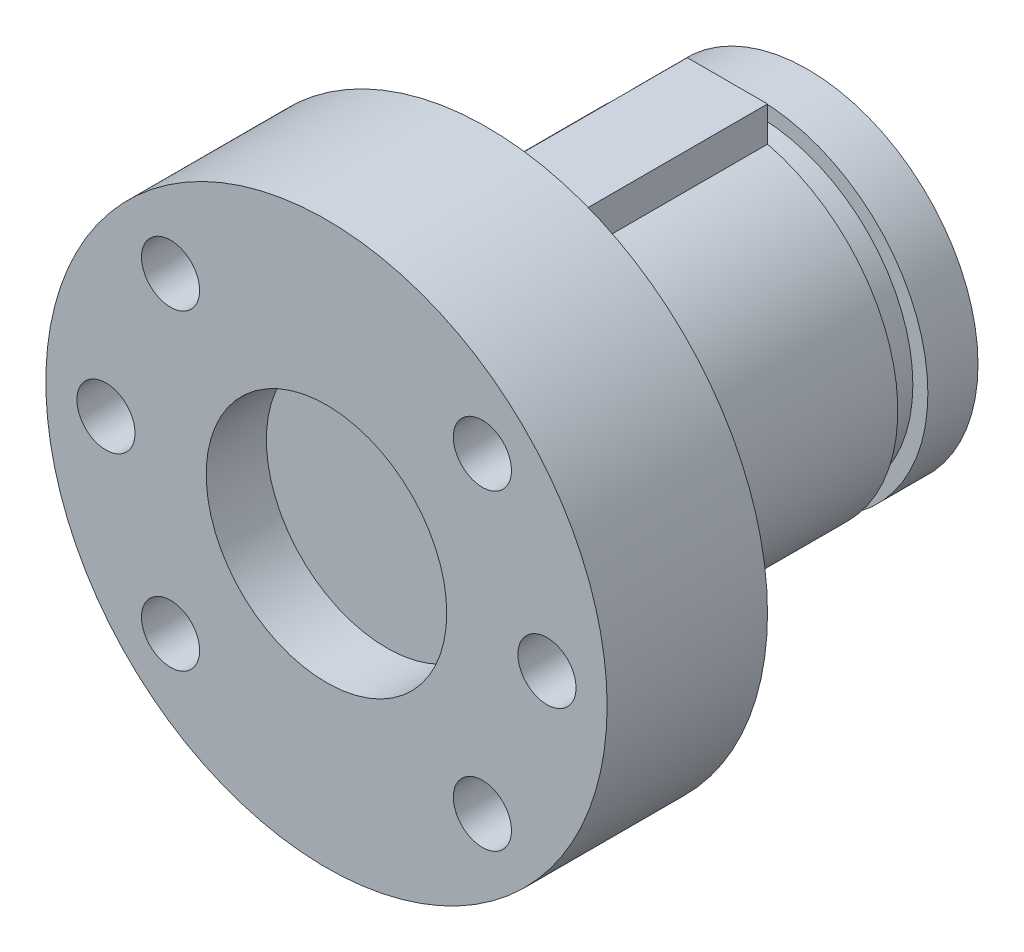
SolidWorks part; units mm, degrees
ref_plane "Front Plane" through (0, 0, 0) normal (0, 0, 1) x (1, 0, 0)
ref_plane "Top Plane" through (0, 0, 0) normal (0, 1, 0) x (1, 0, 0)
ref_plane "Right Plane" through (0, 0, 0) normal (1, 0, 0) x (0, 0, -1)
sketch "Sketch1" plane through (0, 0, 0) normal (0, 1, 0) x (1, 0, 0)
  line L0 (0, -25.8775) -> (0, 0) construction
  line L1 (-72.1845, 0) -> (0, 0) construction
  line L2 (0, 24) -> (0, 3)
  line L3 (6, 0) -> (14, 0)
  line L4 (14, 0) -> (14, 8)
  line L5 (14, 8) -> (8.5, 8)
  line L6 (8.5, 8) -> (8.5, 24)
  line L7 (8.5, 24) -> (0, 24)
  line L8 (0, 3) -> (6, 3)
  line L9 (6, 3) -> (6, 0)
  line L10 (6, 0) -> (78.7219, 0) construction
  line L11 (0, 3) -> (0, 87.9833) construction
  line L12 (-15.3879, 20) -> (15.0503, 20) construction
  dimension "D2" = 8.5
  dimension "D1" = 14
  dimension "D3" = 24
  dimension "D4" = 8
  dimension "D5" = 6
  dimension "D6" = 3
  dimension "D7" = 20
revolve "Revolve1" add sketch "Sketch1" angle 360 about L0
sketch "Sketch2" plane through (0, 0, -8) normal (0, 0, -1) x (-1, 0, 0)
  line L0 (-17.4892, 0) -> (19.5361, 0) construction
  point P3 (11, 0)
  point P4 (7.7782, -7.7782)
  point P7 (0, -11)
  point P8 (-7.7782, -7.7782)
  point P9 (-11, 0)
  point P10 (-7.7782, 7.7782)
  point P11 (0, 11)
  point P12 (7.7782, 7.7782)
  point P13 (0, 0)
  dimension "D1" = 11
  dimension "D2" = 8
hole_wizard "CBORE for M2.5 SHCS1" positions "Sketch3" profile "Sketch4" counterbore size "M2.5" standard "ANSI Metric" end condition through all
sketch "Sketch3" plane through (0, 0, -8) normal (0, 0, -1) x (-1, 0, 0)
  point P0 (11, 0)
  point P3 (7.7782, 7.7782)
  point P9 (-7.7782, 7.7782)
  point P12 (-11, 0)
  point P15 (-7.7782, -7.7782)
  point P21 (7.7782, -7.7782)
sketch "Sketch4" plane through (-11, 0, -8) normal (1, 0, 0) x (0, 1, 0)
  line L0 (0, 0) -> (0, 8)
  line L1 (0, 8) -> (1.45, 8)
  line L3 (1.45, 8) -> (1.45, 2.5)
  line L4 (2.75, 2.5) -> (1.45, 2.5)
  line L5 (2.75, 2.5) -> (2.75, 0.025)
  line L6 (2.75, 0.025) -> (2.775, 0)
  line L7 (2.775, 0) -> (0, 0)
  line L8 (-2.75, 0.025) -> (-2.775, 0) construction
  line L11 (0, -6.35) -> (0, 107.95) construction
  dimension "Thru Hole Dia." = 2.9
  dimension "Thru Hole Depth" = 8
  dimension "C'Bore Dia." = 5.5
  dimension "C'Bore Depth" = 2.5
  dimension "Near C'Sink Dia." = 5.55
  dimension "Near C'Sink Angle" = 90
sketch "Sketch6" plane through (0, 0, 0) normal (0, 1, 0) x (1, 0, 0)
  line L0 (0, -6.0586) -> (0, 30.0983) construction
  line L1 (-16.1345, 0) -> (17.0049, 0) construction
  line L2 (7.75, 21.5) -> (8.5, 21.5)
  line L3 (7.75, 21.5) -> (7.75, 20)
  line L4 (7.75, 20) -> (8.5, 20)
  line L5 (8.5, 21.5) -> (8.5, 20)
  dimension "D1" = 8.5
  dimension "D2" = 7.75
  dimension "D3" = 20
  dimension "D4" = 1.5
revolve "Cut-Revolve1" cut sketch "Sketch6" angle 360 about L0
ref_plane "Plane1" through (0, 0, -20) normal (0, 0, 1) x (1, 0, 0)
sketch "Sketch8" plane through (0, 0, -20) normal (0, 0, 1) x (1, 0, 0)
  line L0 (0, -5.7463) -> (0, 10.1692) construction
  line L1 (6.5898, 0) -> (-5.4418, 0) construction
  line L2 (3.2385, 8.5) -> (-3.6317, 8.5) construction
  line L3 (2, 10) -> (-2, 10)
  line L4 (2, 10) -> (2, 6)
  line L5 (2, 6) -> (-2, 6)
  line L6 (-2, 10) -> (-2, 6)
  circle A0 centre (0, 0) radius 8.5
  point P13 (0, 8.5)
  dimension "D1" = 17
  dimension "D2" = 4
  dimension "D3" = 4
  dimension "D4" = 2.5
  dimension "D5" = 2
extrude "Boss-Extrude1" add sketch "Sketch8" along normal up to surface (12 mm away) contours L3 L6 L5 L4 up to face at (0, 0, -8)
equation "\"shaftB_id\"=6"
equation "\"shaftB_odB\"= 17"
equation "\"D2@Sketch1\"=\"shaftB_odB\"/2"
equation "\"shaftB_odA\"= 28"
equation "\"D1@Sketch1\"=\"shaftB_odA\"/2"
equation "\"shaftB_length\"= 24'4"
equation "\"D3@Sketch1\"=\"shaftB_length\""
equation "\"shaftB_lengthA\"= 8"
equation "\"D4@Sketch1\"=\"shaftB_lengthA\""
equation "\"shaftB_key_b\"=4"
equation "\"shaftB_keyB_b\"=4"
equation "\"shaftB_keyB_t2\"=0.900666"
equation "\"shaftB_keyB_t1\"=2.5"
equation "\"shaftB_keyB_h\"=4"
equation "\"D1@Sketch6\"=\"shaftB_odB\"/2"
equation "\"shaftB_retaining_groove_od\"=15.5"
equation "\"D2@Sketch6\"=\"shaftB_retaining_groove_od\"/2"
equation "\"shaftB_retaining_groove_posZ\" = 20"
equation "\"D3@Sketch6\"=\"shaftB_retaining_groove_posZ\""
equation "\"shaftB_retaining_groove_length\"=1.5"
equation "\"D4@Sketch6\"=\"shaftB_retaining_groove_length\""
equation "\"shaftB_keyway_posZ\"=20"
equation "\"D7@Sketch1\"=\"shaftB_keyway_posZ\""
equation "\"D1@Sketch8\"=\"shaftB_odB\""
equation "\"shaftB_key_h\"=4"
equation "\"D2@Sketch8\"=\"shaftB_keyB_h\""
equation "\"D3@Sketch8\"=\"shaftB_keyB_b\""
equation "\"D4@Sketch8\"=\"shaftB_keyB_t1\""
equation "\"D5@Sketch8\"=\"shaftB_keyB_b\"/2"
